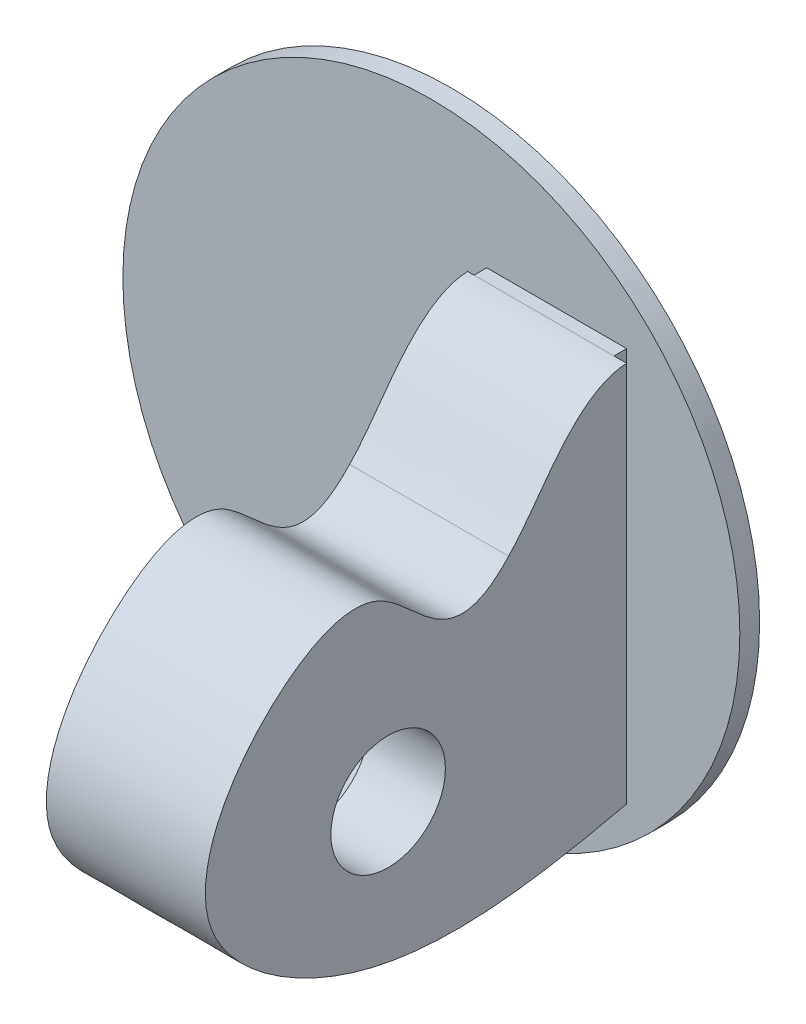
SolidWorks part; units mm, degrees
ref_plane "Front Plane" through (0, 0, 0) normal (0, 0, 1) x (1, 0, 0)
ref_plane "Top Plane" through (0, 0, 0) normal (0, 1, 0) x (1, 0, 0)
ref_plane "Right Plane" through (0, 0, 0) normal (1, 0, 0) x (0, 0, -1)
sketch "Sketch1" plane through (0, 0, 0) normal (0, 0, 1) x (1, 0, 0)
  circle A0 centre (0, 0) radius 48.5
  dimension "D1" = 97
extrude "Boss-Extrude1" add sketch "Sketch1" along normal blind 3.1113
sketch "Sketch2" plane through (0, 0, 3.1113) normal (0, 0, 1) x (1, 0, 0)
  line L5 (30.707, 29.9017) -> (8.707, 29.9017)
  line L6 (30.707, 29.9017) -> (30.707, -30.0983)
  line L7 (30.707, -30.0983) -> (8.707, -30.0983)
  line L8 (8.707, 29.9017) -> (8.707, -30.0983)
  dimension "D1" = 60
  dimension "D2" = 22
extrude "Boss-Extrude6" add sketch "Sketch2" along normal blind 2
sketch "Sketch6" plane through (30.707, 0, 0) normal (1, 0, 0) x (0, 0, -1)
  line L3 (-5.1113, 29.9017) -> (-3.1113, 29.9017) construction
  line L4 (-5.1113, 29.9017) -> (-5.1113, -30.0983)
  spline S0 degree 3 poles (-5.1113, -30.0983) (-21.0677, -33.7436) (-45.9771, -37.935) (-77.0147, -13.9108) (-65.3806, 10.4858) (-41.8971, 23.7978) (-33.0376, 2.7835) (-23.6728, 12.9186) knots 0 0 0 0 0.360058 0.526916 0.718383 0.849564 1 1 1 1
  spline S1 degree 3 poles (-23.6728, 12.9186) (-19.0198, 17.4254) (-13.1044, 30.546) (-3.7719, 29.8774) (-3.1113, 29.9017) knots 0 0 0 0 0.927274 1 1 1 1
extrude "Boss-Extrude7" add sketch "Sketch6" along normal blind 2 and the other way blind 23 contours S1 S0
sketch "Sketch7" plane through (7.707, 0, 0) normal (-1, 0, 0) x (0, 0, 1)
  line L9 (11.4525, -0.4408) -> (52.4525, -0.4408)
  line L10 (11.4525, -0.4408) -> (11.4525, -21.4408)
  line L11 (11.4525, -21.4408) -> (52.4525, -21.4408)
  line L12 (52.4525, -0.4408) -> (52.4525, -21.4408)
  circle A0 centre (-46.7212, -19.1411) radius 9
  dimension "D3" = 18
  dimension "D1" = 21
  dimension "D2" = 41
extrude "Cut-Extrude5" cut sketch "Sketch7" against normal blind 13 contours A0 | L10 L9 L12 L11
sketch "Sketch12" plane through (20.707, 0, 0) normal (-1, 0, 0) x (0, 0, 1)
  circle A0 centre (42.6126, -11.0248) radius 9
  dimension "D1" = 18
extrude "Cut-Extrude6" cut sketch "Sketch12" against normal blind 14
sketch "Sketch13" plane through (7.707, 0, 0) normal (-1, 0, 0) x (0, 0, 1)
  circle A0 centre (55.0227, -6.3535) radius 1.5
  circle A1 centre (55.0227, -15.3535) radius 1.5
  circle A2 centre (9.3004, -6.3535) radius 1.5
  circle A3 centre (9.3004, -15.3535) radius 1.5
  point P8 (0, 0)
  point P9 (0, 0)
  point P10 (0, 0)
  dimension "D3" = 3
  dimension "D4" = 3
  dimension "D5" = 3
  dimension "D6" = 3
  dimension "D1" = 9
  dimension "D2" = 9
extrude "Cut-Extrude7" cut sketch "Sketch13" against normal blind 10
